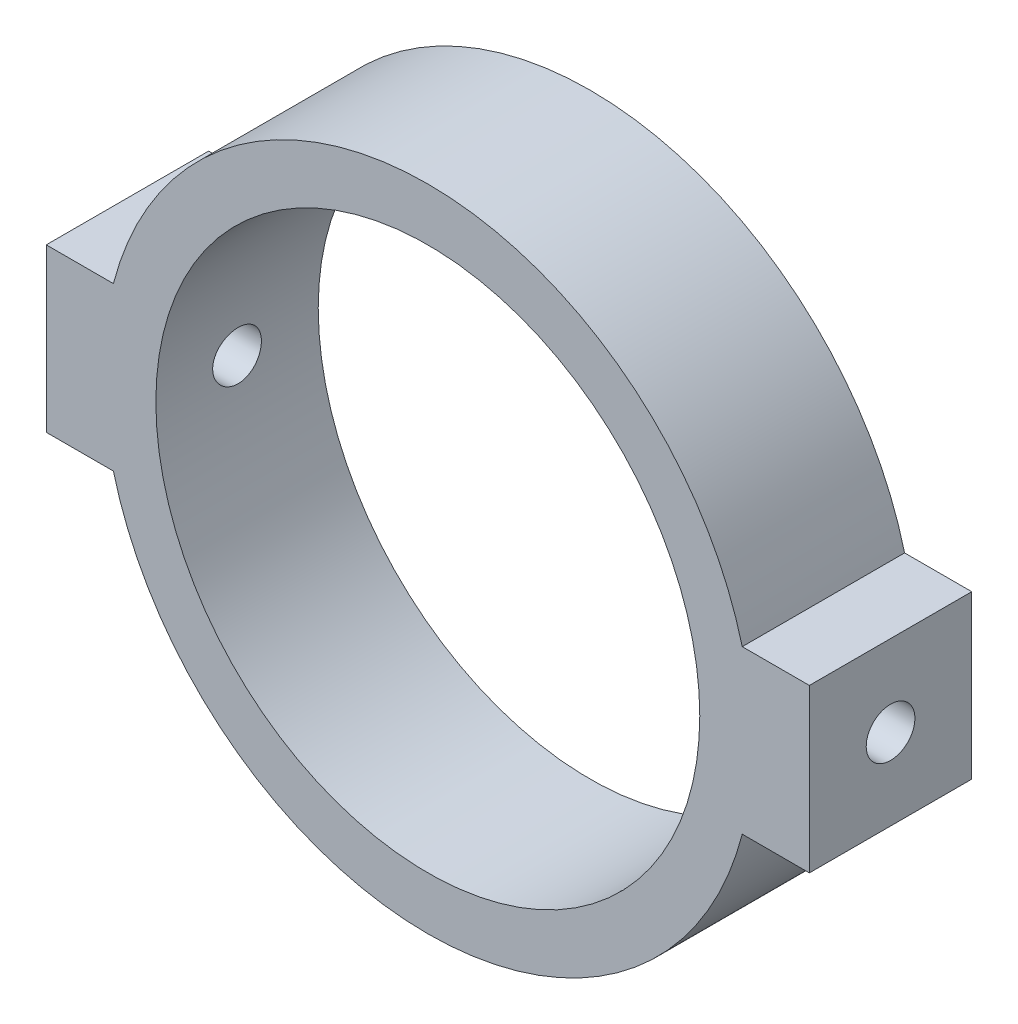
SolidWorks part; units mm, degrees
ref_plane "Alzado" through (0, 0, 0) normal (0, 0, 1) x (1, 0, 0)
ref_plane "Planta" through (0, 0, 0) normal (0, 1, 0) x (1, 0, 0)
ref_plane "Vista lateral" through (0, 0, 0) normal (1, 0, 0) x (0, 0, -1)
sketch "Croquis1" plane through (0, 0, 0) normal (0, 0, 1) x (1, 0, 0)
  line L0 (0, 0) -> (70.4119, 0) construction
  line L1 (-23.5, -5) -> (-19.3649, -5)
  line L2 (23.5, -5) -> (23.5, 5)
  line L3 (23.5, 5) -> (19.3649, 5)
  line L4 (-23.5, 5) -> (-23.5, -5)
  line L5 (-19.3649, 5) -> (-23.5, 5)
  line L6 (19.3649, -5) -> (23.5, -5)
  circle A0 centre (0, 0) radius 16.75
  arc A1 (-19.3649, -5) -> (19.3649, -5) centre (0, 0) ccw
  arc A2 (19.3649, 5) -> (-19.3649, 5) centre (0, 0) ccw
  dimension "D1" = 33.5
  dimension "D2" = 40
  dimension "D3" = 10
  dimension "D4" = 5
  dimension "D5" = 47
  dimension "D6" = 23.5
extrude "Saliente-Extruir1" add sketch "Croquis1" along normal blind 10
sketch "Croquis2" plane through (23.5, 0, 0) normal (1, 0, 0) x (0, 0, -1)
  line L0 (-10, 5) -> (0, -5) construction
  circle A0 centre (-5, 0) radius 1.5
  dimension "D1" = 3
extrude "Cortar-Extruir1" cut sketch "Croquis2" against normal blind 67
